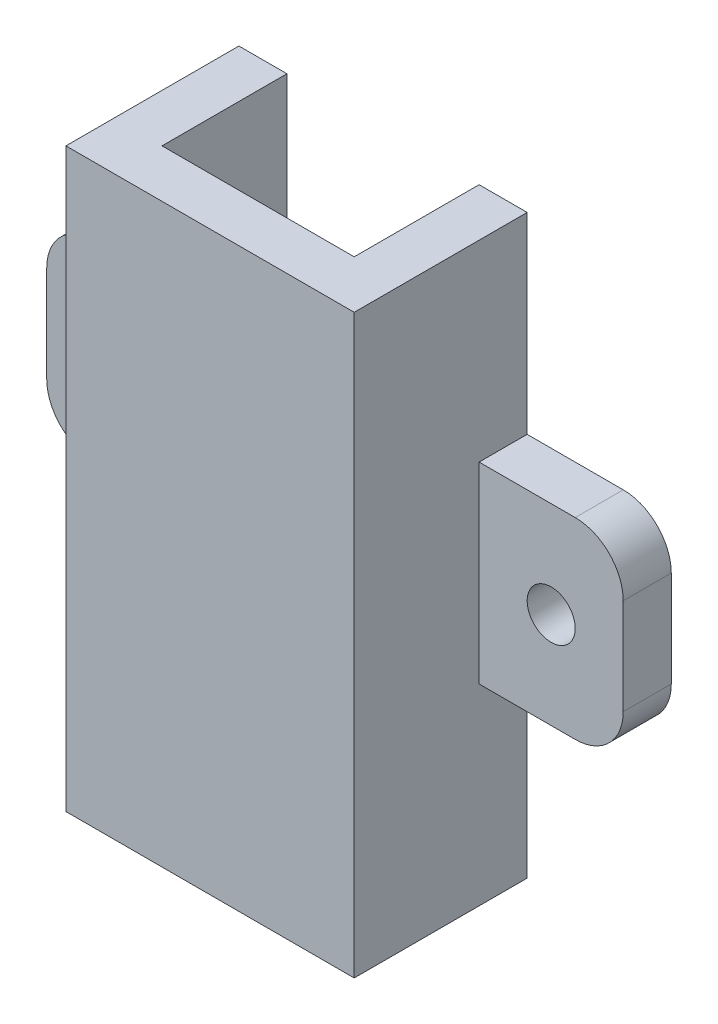
SolidWorks part; units mm, degrees
ref_plane "Front Plane" through (0, 0, 0) normal (0, 0, 1) x (1, 0, 0)
ref_plane "Top Plane" through (0, 0, 0) normal (0, 1, 0) x (1, 0, 0)
ref_plane "Right Plane" through (0, 0, 0) normal (1, 0, 0) x (0, 0, -1)
sketch "Sketch2" plane through (0, 0, 0) normal (0, 1, 0) x (1, 0, 0)
  line L1 (0, 0) -> (38.1, 0)
  line L2 (0, 0) -> (0, 22.86)
  line L3 (0, 22.86) -> (38.1, 22.86)
  line L4 (38.1, 0) -> (38.1, 22.86)
  line L5 (6.35, 22.86) -> (31.75, 22.86)
  line L6 (6.35, 22.86) -> (6.35, 6.35)
  line L7 (6.35, 6.35) -> (31.75, 6.35)
  line L8 (31.75, 22.86) -> (31.75, 6.35)
  dimension "D1" = 38.1
  dimension "D2" = 22.86
  dimension "D3" = 6.35
  dimension "D4" = 6.35
  dimension "D5" = 6.35
extrude "Boss-Extrude1" add sketch "Sketch2" along normal blind 76.2 contours L3 L8 L7 L6 L2 L1 L4
sketch "Sketch3" plane through (0, 0, 0) normal (0, 0, 1) x (1, 0, 0)
  line L1 (38.1, 76.2) -> (0, 76.2) construction
  line L2 (0, 76.2) -> (0, 0) construction
  line L3 (0, 0) -> (38.1, 0) construction
  line L4 (19.05, 50.8) -> (-19.05, 50.8)
  line L6 (-19.05, 25.4) -> (19.05, 25.4)
  arc A1 (19.05, 50.8) -> (19.05, 25.4) centre (19.05, 38.1) cw
  arc A2 (-19.05, 50.8) -> (-19.05, 25.4) centre (-19.05, 38.1) ccw
  circle A3 centre (-19.05, 38.1) radius 2.5019
  point P11 (19.05, 76.2)
  point P12 (19.05, 0)
  point P13 (0, 38.1)
  dimension "D1" = 12.7
  dimension "D3" = 5.0038
  dimension "D2" = 38.1
extrude "Boss-Extrude2" add sketch "Sketch3" against normal blind 6.35
sketch "Sketch4" plane through (0, 0, -22.86) normal (0, 0, -1) x (-1, 0, 0)
  line L0 (-38.1, 76.2) -> (-38.1, 0) construction
  line L1 (-38.1, 50.8) -> (-57.15, 50.8)
  line L2 (-38.1, 50.8) -> (-38.1, 25.4)
  line L3 (-38.1, 25.4) -> (-57.15, 25.4)
  line L4 (-57.15, 50.8) -> (-57.15, 25.4)
  line L5 (-57.15, 38.1) -> (-38.1, 38.1) construction
  line L6 (-47.625, 50.8) -> (-47.625, 25.4) construction
  line L7 (-38.1, 76.2) -> (0, 76.2) construction
  line L8 (-38.1, 0) -> (0, 0) construction
  line L9 (-19.05, 76.2) -> (-19.05, 0) construction
  line L10 (0, 25.4) -> (19.05, 25.4)
  line L11 (19.05, 50.8) -> (19.05, 25.4)
  line L12 (0, 50.8) -> (19.05, 50.8)
  line L13 (0, 50.8) -> (0, 25.4)
  circle A0 centre (-47.625, 38.1) radius 3.175
  circle A1 centre (9.525, 38.1) radius 3.175
  dimension "D4" = 6.35
  dimension "D1" = 25.4
  dimension "D2" = 25.4
  dimension "D3" = 19.05
extrude "Boss-Extrude3" add sketch "Sketch4" against normal blind 6.35
fillet "Fillet1" radius 6.35 4 edges at (57.15, 25.4, -19.685) (57.15, 50.8, -19.685) (-19.05, 25.4, -19.685) (-19.05, 50.8, -19.685)
sketch "Sketch5" plane through (0, 0, 0) normal (0, 0, 1) x (1, 0, 0)
  line L0 (-19.05, 25.4) -> (0, 25.4) construction
  line L1 (0, 50.8) -> (-19.05, 50.8) construction
  line L2 (-19.05, 25.4) -> (0, 25.4)
  line L3 (0, 50.8) -> (-19.05, 50.8)
  line L4 (0, 25.4) -> (0, 50.8)
  arc A0 (-19.05, 50.8) -> (-19.05, 25.4) centre (-19.05, 38.1) ccw construction
  arc A1 (-19.05, 50.8) -> (-19.05, 25.4) centre (-19.05, 38.1) ccw
extrude "Cut-Extrude1" cut sketch "Sketch5" against normal up to next
